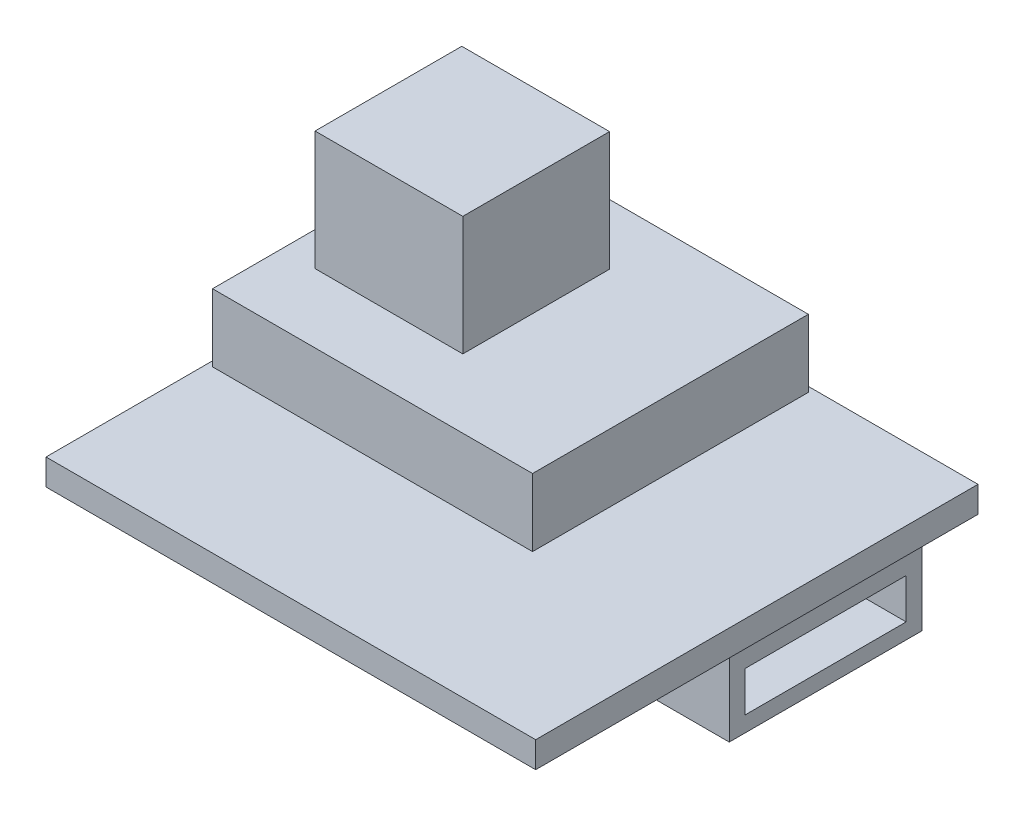
SolidWorks part; units mm, degrees
material "APM Power Unit"
ref_plane "Front Plane" through (0, 0, 0) normal (0, 0, 1) x (1, 0, 0)
ref_plane "Top Plane" through (0, 0, 0) normal (0, 1, 0) x (1, 0, 0)
ref_plane "Right Plane" through (0, 0, 0) normal (1, 0, 0) x (0, 0, -1)
sketch "Sketch1" plane through (0, 0, 0) normal (0, 1, 0) x (1, 0, 0)
  line L1 (0, 0) -> (23.9014, 0)
  line L2 (0, 0) -> (0, 21.59)
  line L3 (0, 21.59) -> (23.9014, 21.59)
  line L4 (23.9014, 0) -> (23.9014, 21.59)
  dimension "D1" = 23.9014
  dimension "D2" = 21.59
extrude "Boss-Extrude1" add sketch "Sketch1" along normal blind 1.27
sketch "Sketch2" plane through (0, 1.27, 0) normal (0, 1, 0) x (1, 0, 0)
  line L0 (23.9014, 21.59) -> (0, 21.59) construction
  line L1 (0.254, 21.336) -> (15.875, 21.336)
  line L2 (0.254, 21.336) -> (0.254, 7.874)
  line L3 (0.254, 7.874) -> (15.875, 7.874)
  line L4 (15.875, 21.336) -> (15.875, 7.874)
  line L5 (0, 21.59) -> (0, 0) construction
  dimension "D1" = 15.621
  dimension "D2" = 13.462
  dimension "D3" = 0.254
  dimension "D4" = 0.254
extrude "Boss-Extrude2" add sketch "Sketch2" along normal blind 3.302
sketch "Sketch3" plane through (0, 4.572, 0) normal (0, 1, 0) x (1, 0, 0)
  line L0 (15.875, 21.336) -> (0.254, 21.336) construction
  line L1 (1.905, 18.3896) -> (9.1186, 18.3896)
  line L2 (1.905, 18.3896) -> (1.905, 11.2268)
  line L3 (1.905, 11.2268) -> (9.1186, 11.2268)
  line L4 (9.1186, 18.3896) -> (9.1186, 11.2268)
  line L5 (0.254, 21.336) -> (0.254, 7.874) construction
  dimension "D1" = 7.2136
  dimension "D2" = 7.1628
  dimension "D3" = 2.9464
  dimension "D4" = 1.651
extrude "Boss-Extrude3" add sketch "Sketch3" along normal blind 5.8166
sketch "Sketch4" plane through (0, 0, 0) normal (0, -1, 0) x (-1, 0, 0)
  line L0 (-23.9014, 0) -> (-23.9014, 21.59) construction
  line L1 (-8.6614, 9.8298) -> (-12.8524, 9.8298)
  line L2 (-8.6614, 9.8298) -> (-8.6614, 16.8656)
  line L3 (-8.6614, 16.8656) -> (-12.8524, 16.8656)
  line L4 (-12.8524, 9.8298) -> (-12.8524, 16.8656)
  line L5 (-23.9014, 21.59) -> (0, 21.59) construction
  dimension "D1" = 4.191
  dimension "D2" = 7.0358
  dimension "D3" = 15.24
  dimension "D4" = 11.7602
extrude "Boss-Extrude4" add sketch "Sketch4" along normal blind 4.5212
sketch "Sketch5" plane through (0, 0, 0) normal (0, -1, 0) x (-1, 0, 0)
  line L1 (-19.0754, 9.7028) -> (-23.6474, 9.7028)
  line L2 (-19.0754, 9.7028) -> (-19.0754, 19.1008)
  line L3 (-19.0754, 19.1008) -> (-23.6474, 19.1008)
  line L4 (-23.6474, 9.7028) -> (-23.6474, 19.1008)
  line L5 (-23.9014, 21.59) -> (0, 21.59) construction
  line L6 (-23.9014, 0) -> (-23.9014, 21.59) construction
  dimension "D1" = 4.572
  dimension "D2" = 9.398
  dimension "D3" = 11.8872
  dimension "D4" = 0.254
extrude "Boss-Extrude5" add sketch "Sketch5" along normal blind 3.81
sketch "Sketch6" plane through (23.6474, 0, 0) normal (1, 0, 0) x (0, 0, -1)
  line L0 (9.7028, -3.81) -> (9.7028, 0) construction
  line L1 (10.4648, -1.0861) -> (18.3388, -1.0861)
  line L2 (10.4648, -1.0861) -> (10.4648, -3.048)
  line L3 (10.4648, -3.048) -> (18.3388, -3.048)
  line L4 (18.3388, -1.0861) -> (18.3388, -3.048)
  line L6 (9.7028, -2.5654) -> (10.4648, -2.5654) construction
  line L7 (9.7028, -0.3241) -> (19.1008, -0.3241) construction
  line L8 (18.3388, -2.2879) -> (19.1008, -2.2879) construction
  line L9 (19.1008, -3.81) -> (19.1008, 0) construction
  line L10 (16.5812, -3.048) -> (16.5812, -3.81) construction
  line L11 (19.1008, -3.81) -> (9.7028, -3.81) construction
  line L12 (13.3211, -0.3241) -> (13.3211, -1.0861) construction
  dimension "D1" = 0.762
extrude "Cut-Extrude1" cut sketch "Sketch6" against normal offset from surface (3.81 mm away) 0.762 up to face at (19.0754, -1.905, -14.4018)
